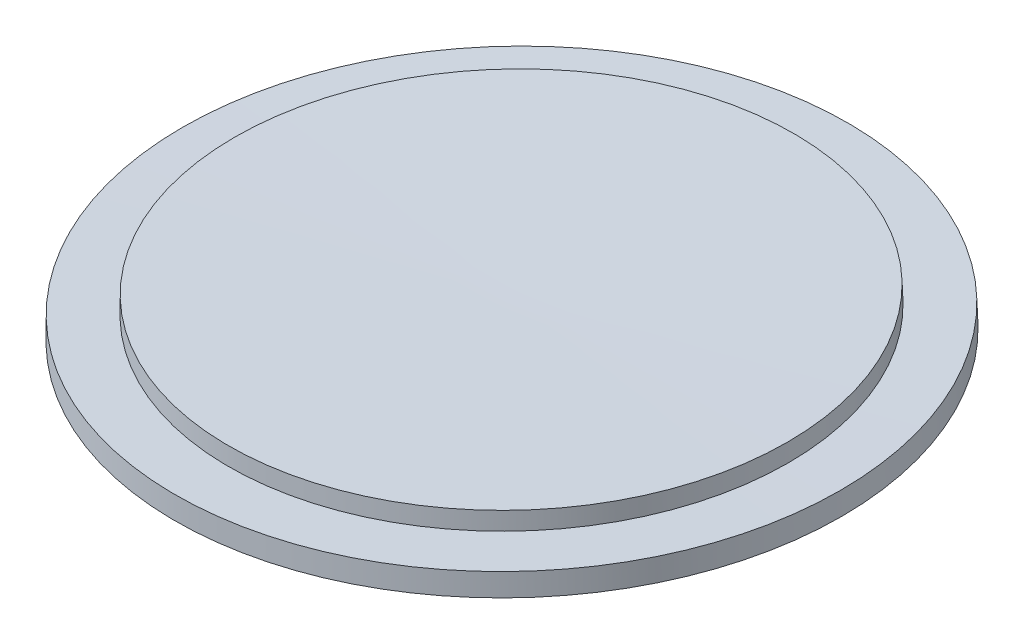
SolidWorks part; units mm, degrees
ref_plane "Front Plane" through (0, 0, 0) normal (0, 0, 1) x (1, 0, 0)
ref_plane "Top Plane" through (0, 0, 0) normal (0, 1, 0) x (1, 0, 0)
ref_plane "Right Plane" through (0, 0, 0) normal (1, 0, 0) x (0, 0, -1)
sketch "Sketch1" plane through (0, 0, 0) normal (0, 0, 1) x (1, 0, 0)
  line L0 (6084.5725, 0) -> (6068.399, 727.0193) construction
  line L1 (1024.0469, 727.0193) -> (11112.7512, 727.0193)
  line L2 (1024.0469, 727.0193) -> (1024.0469, 405.6499)
  line L3 (1024.0469, 405.6499) -> (11112.7512, 405.6499)
  line L4 (11112.7512, 727.0193) -> (11112.7512, 405.6499)
  line L5 (71.4161, 405.6499) -> (11812.8774, 405.6499)
  line L6 (71.4161, 405.6499) -> (71.4161, 0)
  line L7 (71.4161, 0) -> (11812.8774, 0)
  line L8 (11812.8774, 405.6499) -> (11812.8774, 0)
  dimension "D1" = 11741.4613
revolve "Revolve1" add sketch "Sketch1" angle 360 about L0
scale "Scale1" scale about origin uniform scaling yes scale factor 0.1
